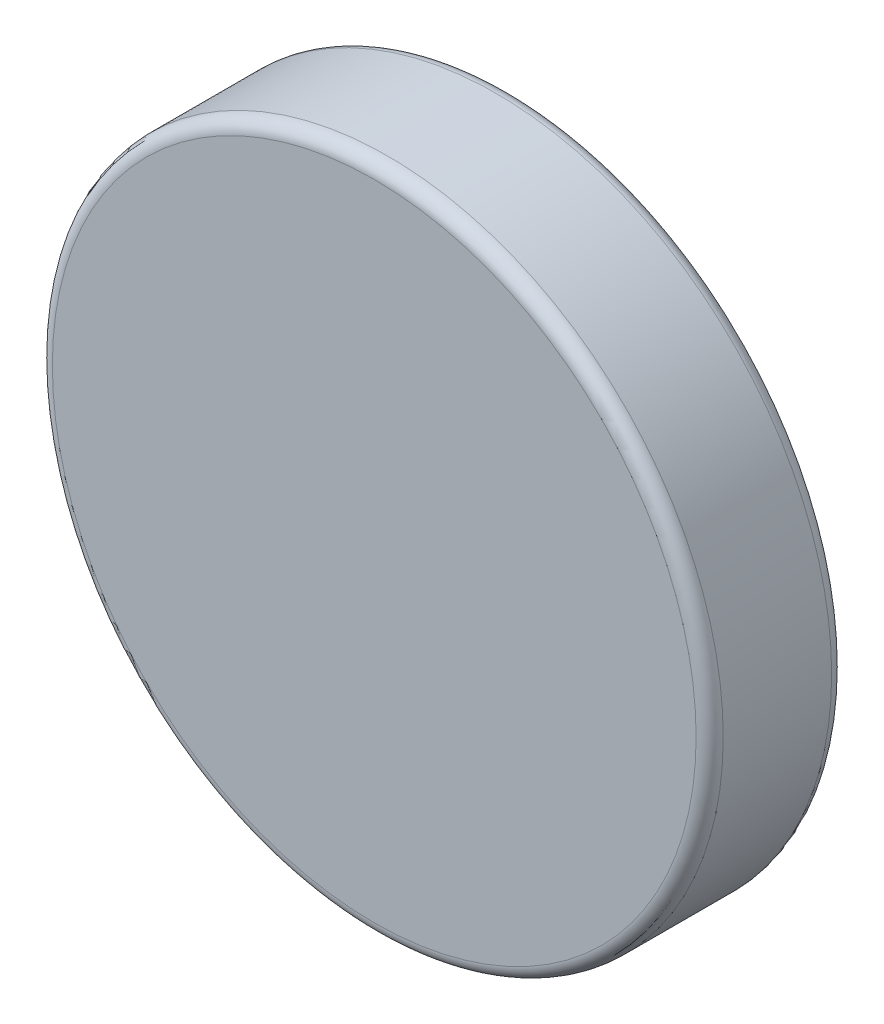
SolidWorks part; units mm, degrees
ref_plane "Plan de face" through (0, 0, 0) normal (0, 0, 1) x (1, 0, 0)
ref_plane "Plan de dessus" through (0, 0, 0) normal (0, 1, 0) x (1, 0, 0)
ref_plane "Plan de droite" through (0, 0, 0) normal (1, 0, 0) x (0, 0, -1)
sketch "Esquisse1" plane through (0, 0, 0) normal (0, 0, 1) x (1, 0, 0)
  circle A0 centre (0, 0) radius 4.95
  dimension "D1" = 9.9
extrude "Boss.-Extru.1" add sketch "Esquisse1" along normal blind 2
fillet "Congé1" radius 0.2 2 edges at (4.95, 0, 0) (4.95, 0, 2)
